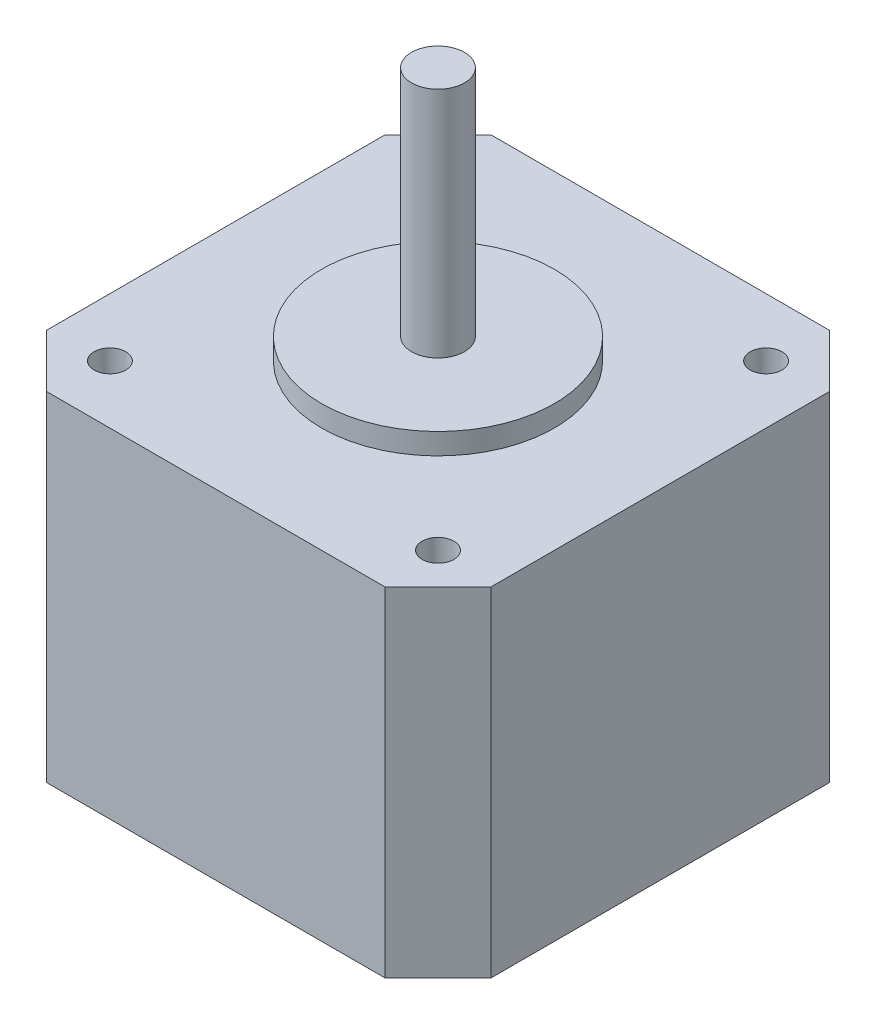
SolidWorks part; units mm, degrees
material "AISI 1020"
ref_plane "Front Plane" through (0, 0, 0) normal (0, 0, 1) x (1, 0, 0)
ref_plane "Top Plane" through (0, 0, 0) normal (0, 1, 0) x (1, 0, 0)
ref_plane "Right Plane" through (0, 0, 0) normal (1, 0, 0) x (0, 0, -1)
sketch "Sketch1" plane through (0, 0, 0) normal (0, 1, 0) x (1, 0, 0)
  line L1 (-21, -21) -> (21, -21)
  line L2 (-21, -21) -> (-21, 21)
  line L3 (-21, 21) -> (21, 21)
  line L4 (21, -21) -> (21, 21)
  line L5 (-21, -21) -> (21, 21) construction
  line L6 (-21, 21) -> (21, -21) construction
  point P0 (0, 0)
  dimension "D1" = 42
  dimension "D2" = 42
extrude "Boss-Extrude1" add sketch "Sketch1" along normal blind 32
sketch "Sketch2" plane through (0, 32, 0) normal (0, 1, 0) x (1, 0, 0)
  circle A0 centre (0, 0) radius 11
extrude "Boss-Extrude2" add sketch "Sketch2" along normal blind 2
sketch "Sketch3" plane through (0, 34, 0) normal (0, 1, 0) x (1, 0, 0)
  circle A0 centre (0, 0) radius 2.5
extrude "Boss-Extrude3" add sketch "Sketch3" along normal blind 22
sketch "Sketch4" plane through (0, 32, 0) normal (0, 1, 0) x (1, 0, 0)
  circle A0 centre (15.5, 15.5) radius 1.5
  circle A1 centre (15.5, -15.5) radius 1.5
  circle A2 centre (-15.5, -15.5) radius 1.5
  circle A3 centre (-15.5, 15.5) radius 1.5
  dimension "D1" = 31
extrude "Cut-Extrude1" cut sketch "Sketch4" against normal blind 5
chamfer "Chamfer1" distance 5 4 edges at (21, 16, 21) (-21, 16, 21) (-21, 16, -21) (21, 16, -21)
